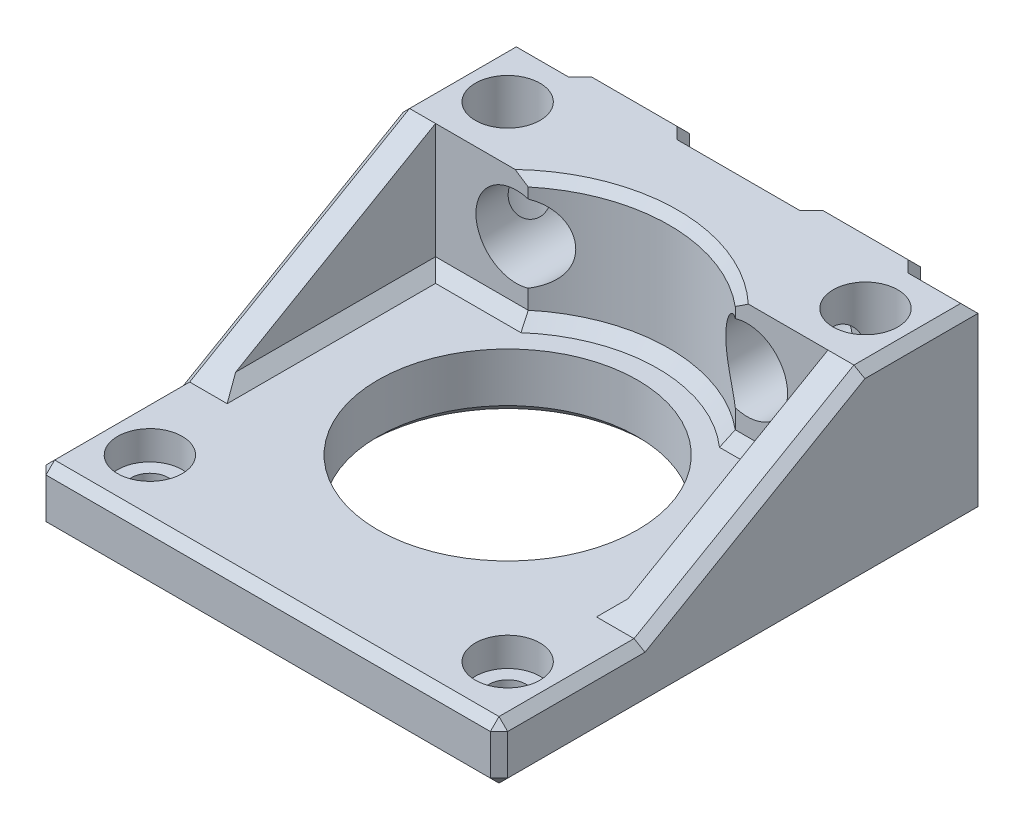
SolidWorks part; units mm, degrees
ref_plane "Front Plane" through (0, 0, 0) normal (0, 0, 1) x (1, 0, 0)
ref_plane "Top Plane" through (0, 0, 0) normal (0, 1, 0) x (1, 0, 0)
ref_plane "Right Plane" through (0, 0, 0) normal (1, 0, 0) x (0, 0, -1)
sketch "Sketch1" plane through (0, 0, 0) normal (0, 1, 0) x (1, 0, 0)
  line L0 (0, 0) -> (0, 11.25) construction
  line L1 (-20, 20.75) -> (-15, 20.75)
  line L2 (-20, 20.75) -> (-20, -20.75)
  line L3 (-20, -20.75) -> (20, -20.75)
  line L4 (20, 20.75) -> (20, -20.75)
  line L5 (0, 11.25) -> (0, 20.75) construction
  line L6 (-15, 20.75) -> (-14, 21.75)
  line L7 (-5, 20.75) -> (5, 20.75)
  line L8 (5, 20.75) -> (6, 21.75)
  line L9 (15, 20.75) -> (20, 20.75)
  line L10 (-14, 21.75) -> (-6, 21.75)
  line L11 (-6, 21.75) -> (-5, 20.75)
  line L12 (6, 21.75) -> (14, 21.75)
  line L13 (14, 21.75) -> (15, 20.75)
  line L14 (0, -20.75) -> (0, -11.25) construction
  line L15 (-15.5, -15.5) -> (15.5, -15.5) construction
  line L16 (-15.5, -15.5) -> (-15.5, 15.5) construction
  line L17 (-15.5, 15.5) -> (15.5, 15.5) construction
  line L18 (15.5, -15.5) -> (15.5, 15.5) construction
  line L19 (-15.5, -15.5) -> (15.5, 15.5) construction
  line L20 (-15.5, 15.5) -> (15.5, -15.5) construction
  circle A0 centre (0, 0) radius 11.25
  circle A1 centre (15.5, 15.5) radius 1.6
  circle A2 centre (-15.5, 15.5) radius 1.6
  circle A3 centre (-15.5, -15.5) radius 1.6
  circle A4 centre (15.5, -15.5) radius 1.6
  point P19 (0, 20.75)
  dimension "D1" = 22.5
  dimension "D10" = 3.2
  dimension "D2" = 9.5
  dimension "D3" = 40
  dimension "D5" = 30
  dimension "D6" = 10
  dimension "D7" = 1
  dimension "D9" = 31
  dimension "D4" = 135
extrude "Boss-Extrude1" add sketch "Sketch1" along normal blind 5
sketch "Sketch4" plane through (0, 5, 0) normal (0, 1, 0) x (1, 0, 0)
  circle A0 centre (-15.5, -15.5) radius 2.8
  circle A1 centre (15.5, 15.5) radius 2.8
  circle A2 centre (-15.5, 15.5) radius 2.8
  circle A3 centre (15.5, -15.5) radius 2.8
  circle A4 centre (15.5, -15.5) radius 1.6 construction
  circle A5 centre (-15.5, -15.5) radius 1.6 construction
  circle A6 centre (-15.5, 15.5) radius 1.6 construction
  circle A7 centre (15.5, 15.5) radius 1.6 construction
  dimension "D1" = 5.6
extrude "Cut-Extrude1" cut sketch "Sketch4" against normal offset from surface (2.5 mm away) 2.5 up to face at (0, 0, -14.1667)
sketch "Sketch2" plane through (0, 5, 0) normal (0, 1, 0) x (1, 0, 0)
  line L0 (0, 14) -> (0, 0) construction
  line L1 (-8.9687, 10.75) -> (-20, 10.75)
  line L2 (-20, 20.75) -> (-20, -20.75) construction
  line L3 (-20, 10.75) -> (-20, 20.75)
  line L5 (20, 20.75) -> (20, 10.75)
  line L6 (20, -20.75) -> (20, 20.75) construction
  line L7 (20, 10.75) -> (8.9687, 10.75)
  line L12 (-20, 20.75) -> (-15, 20.75)
  line L13 (-15, 20.75) -> (-14, 21.75)
  line L14 (-14, 21.75) -> (-6, 21.75)
  line L15 (-6, 21.75) -> (-5, 20.75)
  line L16 (-5, 20.75) -> (5, 20.75)
  line L17 (5, 20.75) -> (6, 21.75)
  line L18 (6, 21.75) -> (14, 21.75)
  line L19 (14, 21.75) -> (15, 20.75)
  line L20 (15, 20.75) -> (20, 20.75)
  arc A0 (-8.9687, 10.75) -> (8.9687, 10.75) centre (0, 0) cw
  circle A1 centre (-15.5, 15.5) radius 2.8
  circle A2 centre (15.5, 15.5) radius 2.8
  circle A5 centre (-15.5, 15.5) radius 2.8 construction
  circle A6 centre (15.5, 15.5) radius 2.8 construction
  line M3 (-20, 20.75) -> (-20, -20.75)
  line M5 (20, -20.75) -> (20, 20.75)
  line M6 (-15, 20.75) -> (-20, 20.75)
  line M8 (20, 20.75) -> (15, 20.75)
  line M9 (15, 20.75) -> (14, 21.75)
  line M10 (14, 21.75) -> (6, 21.75)
  line M11 (6, 21.75) -> (5, 20.75)
  line M12 (5, 20.75) -> (-5, 20.75)
  line M13 (-5, 20.75) -> (-6, 21.75)
  line M14 (-6, 21.75) -> (-14, 21.75)
  line M15 (-14, 21.75) -> (-15, 20.75)
  circle M44 centre (-15.5, 15.5) radius 2.8
  circle M45 centre (15.5, 15.5) radius 2.8
  dimension "D1" = 14
  dimension "D2" = 10
extrude "Boss-Extrude2" add sketch "Sketch2" along normal offset from surface (11 mm away) 16 contours L1 A0 L7 M5 M8 M9 M10 M11 M12 M13 M14 M15 M6 M3 M45 M44 up to face at (0, 0, -14.1667)
sketch "Sketch3" plane through (20, 0, 0) normal (1, 0, 0) x (0, 0, -1)
  line L0 (10.75, 16) -> (-8.3026, 5)
  line L1 (-20.75, 5) -> (10.75, 5) construction
  line L2 (-8.3026, 5) -> (10.75, 5)
  line L4 (10.75, 5) -> (10.75, 16)
  dimension "D1" = 60
extrude "Boss-Extrude3" add sketch "Sketch3" against normal blind 3
mirror "Mirror1" about plane through (0, 0, 0) normal (1, 0, 0) of "Boss-Extrude3"
chamfer "Chamfer2" distance 1 angle 45 5 edges at (17, 5, -1.2237) (12.9843, 5, -10.75) (0, 5, -14) (-12.9843, 5, -10.75) (-17, 5, -1.2237)
sketch "Sketch5" plane through (0, 0, -10.75) normal (0, 0, 1) x (1, 0, 0)
  line L0 (-10, 16) -> (-10, 11) construction
  line L2 (10, 11) -> (17, 11) construction
  line L3 (17, 6) -> (17, 16) construction
  line L4 (10, 11) -> (-10, 11) construction
  line L5 (-10, 11) -> (-17, 11) construction
  line L6 (-8.9687, 16) -> (-17, 16) construction
  line L7 (-17, 6) -> (-17, 16) construction
  line L8 (-10, 11) -> (-10, 5) construction
  line L9 (-8.5987, 5) -> (-16, 5) construction
  circle A0 centre (-10, 11) radius 2.1
  circle A1 centre (10, 11) radius 2.1
  dimension "D2" = 4.2
  dimension "D1" = 20
  dimension "D3" = 5
extrude "Cut-Extrude2" cut sketch "Sketch5" against normal up to next
sketch "Sketch6" plane through (0, 0, -10.75) normal (0, 0, 1) x (1, 0, 0)
  circle A0 centre (-10, 11) radius 3.5
  circle A1 centre (10, 11) radius 3.5
  arc A2 (-8.9687, 12.8293) -> (-8.9687, 9.1707) centre (-10, 11) ccw construction
  arc A3 (8.9687, 9.1707) -> (8.9687, 12.8293) centre (10, 11) ccw construction
  dimension "D1" = 7
extrude "Cut-Extrude3" cut sketch "Sketch6" against normal offset from surface (7 mm away) 3 up to face at (17.5, 8, -20.75)
chamfer "Chamfer3" distance 0.75 angle 45 36 edges at (15.5, 0, 17.1) (-15.5, 0, 17.1) (-15.5, 0, -13.9) (15.5, 0, -13.9) (0, 0, 11.25) (0, 0, 20.75) (20, 0, 0) (17.5, 0, -20.75) (14.5, 0, -21.25) (10, 0, -21.75) (5.5, 0, -21.25) (0, 0, -20.75) (-5.5, 0, -21.25) (-10, 0, -21.75) (-14.5, 0, -21.25) (-17.5, 0, -20.75) (-20, 0, 0) (20, 2.5, 20.75) (-20, 2.5, 20.75) (-20, 5, 14.5263) (-20, 10.5, -1.2237) (20, 10.5, -1.2237) (20, 5, 14.5263) (0, 5, 20.75) (0, 16, -14) (-17.5, 16, -20.75) (-14.5, 16, -21.25) (-10, 16, -21.75) (-5.5, 16, -21.25) (0, 16, -20.75) (5.5, 16, -21.25) (10, 16, -21.75) (14.5, 16, -21.25) (17.5, 16, -20.75) (20, 16, -15.75) (-20, 16, -15.75)
equation "\"Tolerance\"=0.2"
equation "\"D10@Sketch1\"=3 + \"Tolerance\""
equation "\"D1@Sketch4\"=5.4 + \"Tolerance\""
equation "\"D2@Sketch5\"=4 + \"Tolerance\""
equation "\"D1@Sketch6\"=6.8 + \"Tolerance\""
